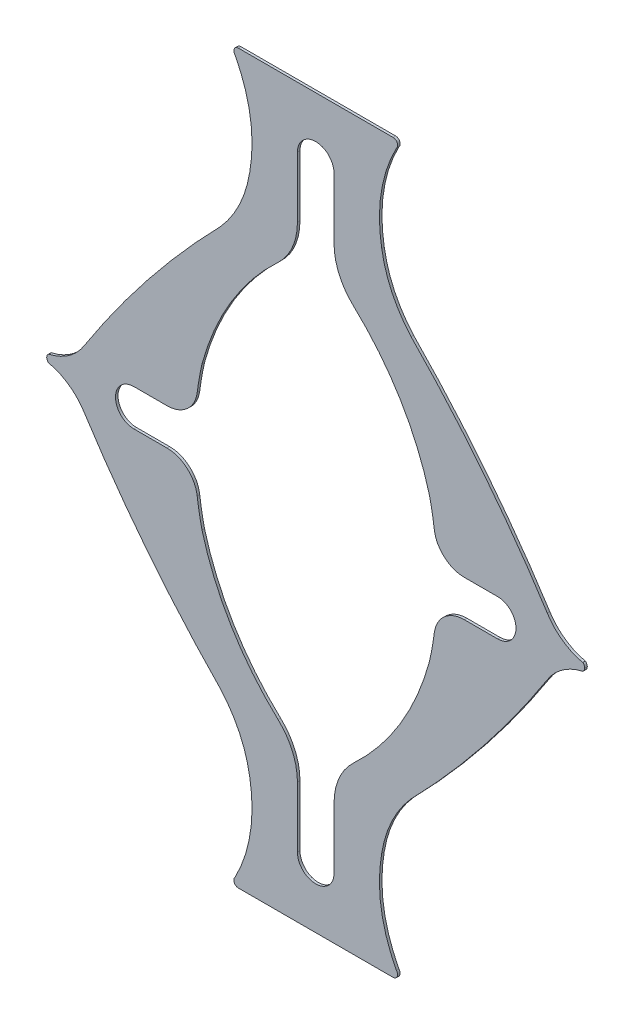
SolidWorks part; units mm, degrees
ref_plane "Front Plane" through (0, 0, 0) normal (0, 0, 1) x (1, 0, 0)
ref_plane "Top Plane" through (0, 0, 0) normal (0, 1, 0) x (1, 0, 0)
ref_plane "Right Plane" through (0, 0, 0) normal (1, 0, 0) x (0, 0, -1)
sketch "Model" plane through (0, 0, 0) normal (0, 0, 1) x (1, 0, 0)
  line L0 (-457.3561, 0) -> (457.3561, 0) construction
  line L1 (0, 914.4) -> (-194.4798, 914.4)
  line L2 (0, 914.4) -> (194.4798, 914.4)
  line L3 (0, -914.4) -> (-194.4798, -914.4)
  line L4 (0, -914.4) -> (194.4798, -914.4)
  line L5 (-46.0375, -762) -> (-46.0375, -609.3611)
  line L6 (46.0375, -762) -> (46.0375, -609.3611)
  line L7 (-457.3561, 46.0375) -> (-373.6086, 46.0375)
  line L8 (-457.3561, -46.0375) -> (-373.6086, -46.0375)
  line L9 (457.3561, 46.0375) -> (373.6086, 46.0375)
  line L10 (457.3561, -46.0375) -> (373.6086, -46.0375)
  line L11 (-46.0375, 762) -> (-46.0375, 609.3611)
  line L12 (46.0375, 762) -> (46.0375, 609.3611)
  line L13 (-165.892, 658.247) -> (-165.9389, 658.1298)
  line L14 (165.892, 658.247) -> (165.9389, 658.1298)
  line L15 (165.9389, -658.1298) -> (165.892, -658.247)
  line L16 (-165.9389, -658.1298) -> (-165.892, -658.247)
  arc A0 (-194.4798, 914.4) -> (-202.9832, 895.3321) centre (-194.4798, 902.97) ccw
  arc A1 (-165.892, 658.247) -> (-202.9832, 895.3321) centre (-527.5303, 723.1138) ccw
  arc A2 (-239.6834, 503.1053) -> (-165.9389, 658.1298) centre (-465.825, 705.7322) ccw
  arc A3 (-239.6834, 503.1053) -> (-582.0374, 72.7477) centre (1699.953, -1391.2476) ccw
  arc A4 (-671.3071, 9.5736) -> (-582.0374, 72.7477) centre (-702.2766, 147.9952) ccw
  arc A5 (-671.3071, 9.5736) -> (-676.2743, 0) centre (-664.8452, 0.1455) ccw
  arc A6 (-94.7889, 497.635) -> (-285.9807, 180.6809) centre (360.5192, 6.8439) ccw
  arc A7 (-285.9807, 180.6809) -> (-298.0062, 112.7126) centre (389.9953, 26.0335) ccw
  arc A8 (-373.6086, 46.0375) -> (-298.0062, 112.7126) centre (-373.6086, 122.2375) ccw
  arc A9 (202.9832, 895.3321) -> (194.4798, 914.4) centre (194.4798, 902.97) ccw
  arc A10 (202.9832, 895.3321) -> (165.892, 658.247) centre (527.5303, 723.1138) ccw
  arc A11 (165.9389, 658.1298) -> (239.6834, 503.1053) centre (465.825, 705.7322) ccw
  arc A12 (582.0374, 72.7477) -> (239.6834, 503.1053) centre (-1699.953, -1391.2476) ccw
  arc A13 (582.0374, 72.7477) -> (671.3071, 9.5736) centre (702.2766, 147.9952) ccw
  arc A14 (676.2743, 0) -> (671.3071, 9.5736) centre (664.8452, 0.1455) ccw
  arc A15 (285.9807, 180.6809) -> (94.7889, 497.635) centre (-360.5192, 6.8439) ccw
  arc A16 (298.0062, 112.7126) -> (285.9807, 180.6809) centre (-389.9953, 26.0335) ccw
  arc A17 (-202.9832, -895.3321) -> (-194.4798, -914.4) centre (-194.4798, -902.97) ccw
  arc A18 (-202.9832, -895.3321) -> (-165.892, -658.247) centre (-527.5303, -723.1138) ccw
  arc A19 (-165.9389, -658.1298) -> (-239.6834, -503.1053) centre (-465.825, -705.7322) ccw
  arc A20 (-582.0374, -72.7477) -> (-239.6834, -503.1053) centre (1699.953, 1391.2476) ccw
  arc A21 (-582.0374, -72.7477) -> (-671.3071, -9.5736) centre (-702.2766, -147.9952) ccw
  arc A22 (-676.2743, 0) -> (-671.3071, -9.5736) centre (-664.8452, -0.1455) ccw
  arc A23 (-285.9807, -180.6809) -> (-94.7889, -497.635) centre (360.5192, -6.8439) ccw
  arc A24 (-46.0375, -609.3611) -> (-94.7889, -497.635) centre (-198.4375, -609.3611) ccw
  arc A25 (-298.0062, -112.7126) -> (-285.9807, -180.6809) centre (389.9953, -26.0335) ccw
  arc A26 (-298.0062, -112.7126) -> (-373.6086, -46.0375) centre (-373.6086, -122.2375) ccw
  arc A27 (194.4798, -914.4) -> (202.9832, -895.3321) centre (194.4798, -902.97) ccw
  arc A28 (165.892, -658.247) -> (202.9832, -895.3321) centre (527.5303, -723.1138) ccw
  arc A29 (239.6834, -503.1053) -> (165.9389, -658.1298) centre (465.825, -705.7322) ccw
  arc A30 (239.6834, -503.1053) -> (582.0374, -72.7477) centre (-1699.953, 1391.2476) ccw
  arc A31 (671.3071, -9.5736) -> (582.0374, -72.7477) centre (702.2766, -147.9952) ccw
  arc A32 (671.3071, -9.5736) -> (676.2743, 0) centre (664.8452, -0.1455) ccw
  arc A33 (94.7889, -497.635) -> (285.9807, -180.6809) centre (-360.5192, -6.8439) ccw
  arc A34 (94.7889, -497.635) -> (46.0375, -609.3611) centre (198.4375, -609.3611) ccw
  arc A35 (285.9807, -180.6809) -> (298.0062, -112.7126) centre (-389.9953, -26.0335) ccw
  arc A36 (46.0375, 762) -> (-46.0375, 762) centre (0, 762) ccw
  arc A37 (-457.3561, 46.0375) -> (-457.3561, -46.0375) centre (-457.3561, 0) ccw
  arc A38 (457.3561, -46.0375) -> (457.3561, 46.0375) centre (457.3561, 0) ccw
  arc A39 (-46.0375, -762) -> (46.0375, -762) centre (0, -762) ccw
  arc A40 (298.0062, 112.7126) -> (373.6086, 46.0375) centre (373.6086, 122.2375) ccw
  arc A41 (373.6086, -46.0375) -> (298.0062, -112.7126) centre (373.6086, -122.2375) ccw
  arc A42 (-94.7889, 497.635) -> (-46.0375, 609.3611) centre (-198.4375, 609.3611) ccw
  arc A43 (46.0375, 609.3611) -> (94.7889, 497.635) centre (198.4375, 609.3611) ccw
  point P2 (0, 0)
extrude "Boss-Extrude1" add sketch "Model" along normal blind 6.35
